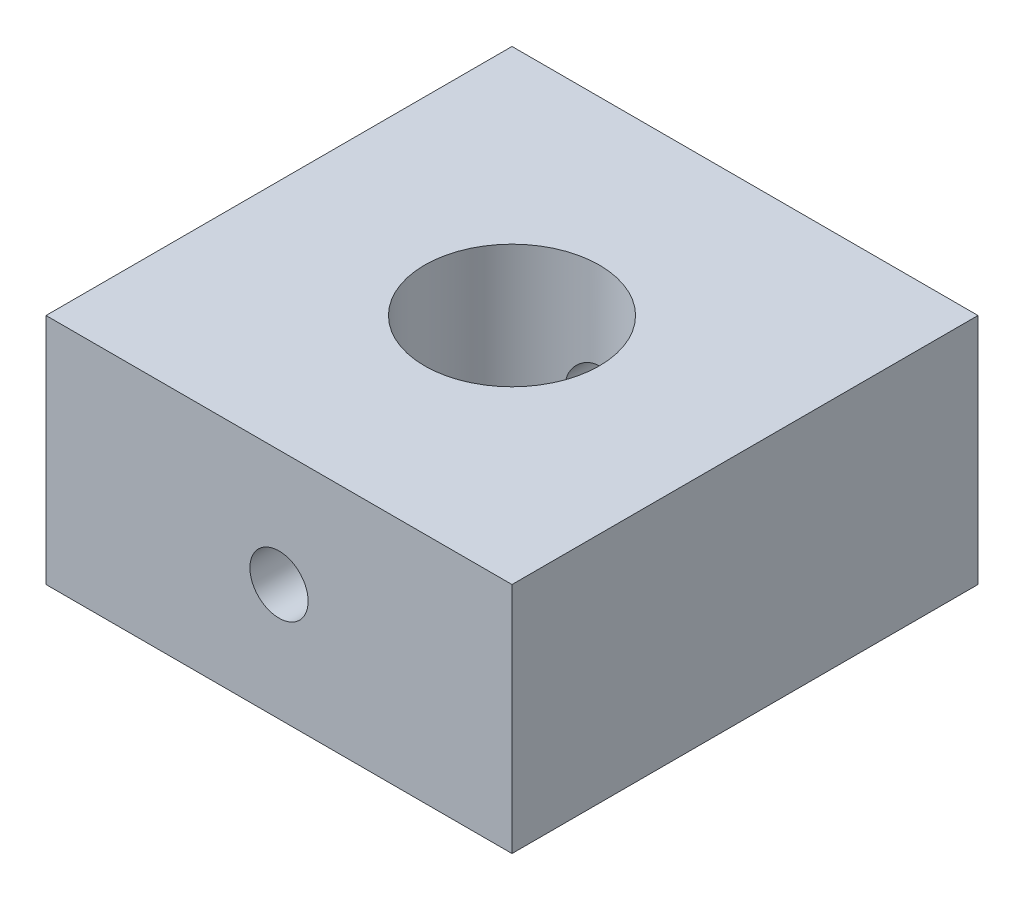
SolidWorks part; units mm, degrees
ref_plane "Front Plane" through (0, 0, 0) normal (0, 0, 1) x (1, 0, 0)
ref_plane "Top Plane" through (0, 0, 0) normal (0, 1, 0) x (1, 0, 0)
ref_plane "Right Plane" through (0, 0, 0) normal (1, 0, 0) x (0, 0, -1)
sketch "Sketch1" plane through (0, 0, 0) normal (0, 1, 0) x (1, 0, 0)
  line L0 (25.4, 25.4) -> (0, 0) construction
  line L1 (0, 0) -> (25.4, 0)
  line L2 (0, 0) -> (0, 25.4)
  line L3 (0, 25.4) -> (25.4, 25.4)
  line L4 (25.4, 0) -> (25.4, 25.4)
  circle A0 centre (12.7, 12.7) radius 4.7625
  dimension "D3" = 9.525
  dimension "D1" = 25.4
  dimension "D2" = 25.4
extrude "Boss-Extrude1" add sketch "Sketch1" along normal blind 12.7
sketch "Sketch2" plane through (0, 0, 0) normal (0, 0, 1) x (1, 0, 0)
  line L0 (12.7, 12.7) -> (12.7, 0) construction
  line L1 (0, 12.7) -> (25.4, 12.7) construction
  line L2 (0, 0) -> (25.4, 0) construction
  circle A0 centre (12.7, 6.35) radius 1.5875
  dimension "D1" = 3.175
extrude "Cut-Extrude1" cut sketch "Sketch2" against normal through all
